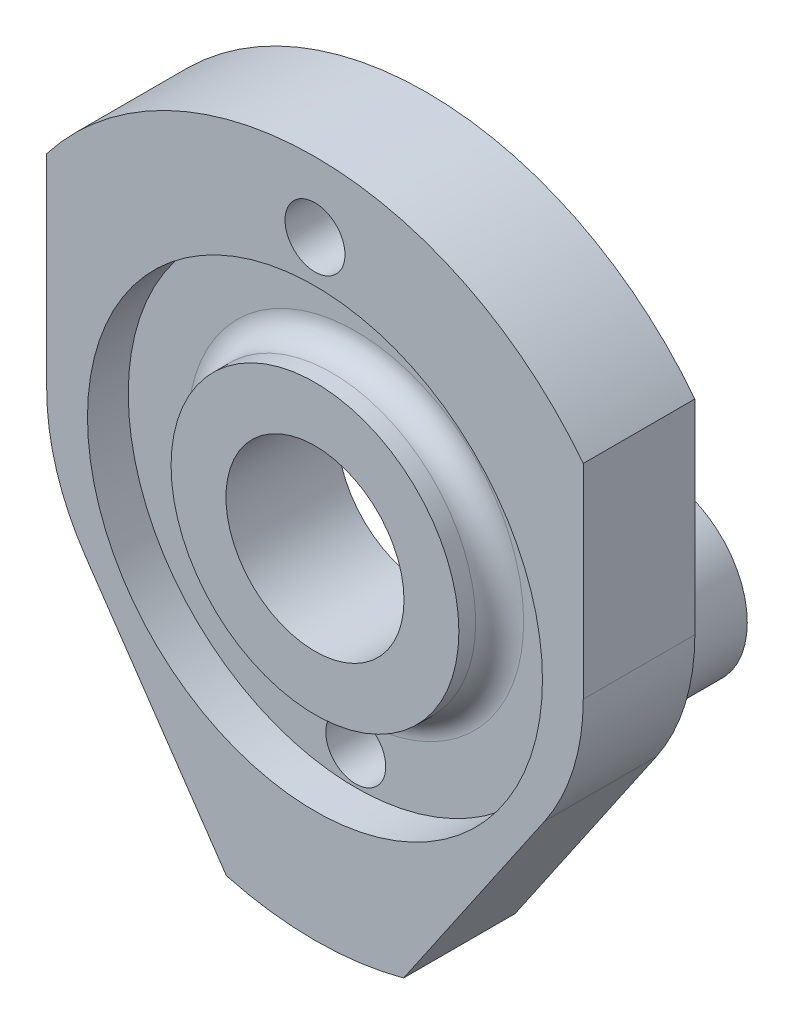
SolidWorks part; units mm, degrees
ref_plane "Front Plane" through (0, 0, 0) normal (0, 0, 1) x (1, 0, 0)
ref_plane "Top Plane" through (0, 0, 0) normal (0, 1, 0) x (1, 0, 0)
ref_plane "Right Plane" through (0, 0, 0) normal (1, 0, 0) x (0, 0, -1)
sketch "Sketch1" plane through (0, 0, 0) normal (0, 0, 1) x (1, 0, 0)
  line L1 (0, 0) -> (5.3097, 0) construction
  line L3 (44.7444, 34.6627) -> (44.7444, 0.6173)
  line L4 (-44.74, 0.611) -> (-44.74, 34.6683)
  line L5 (-14.7812, -54.6358) -> (-38.299, -20.2273)
  line L6 (14.7812, -54.6358) -> (38.3034, -20.2209)
  arc A0 (-14.7812, -54.6358) -> (14.7812, -54.6358) centre (0, 0) ccw
  circle A1 centre (0, 44.95) radius 5
  circle A2 centre (0, 0) radius 14.85
  arc A3 (-44.74, 0.611) -> (-38.299, -20.2273) centre (-7.8109, 0.611) ccw
  arc A4 (44.7444, 0.6173) -> (38.3034, -20.2209) centre (7.8153, 0.6173) cw
  arc A5 (44.7444, 34.6627) -> (-44.74, 34.6683) centre (0, 0) ccw
extrude "Boss-Extrude1" add sketch "Sketch1" against normal blind 18.61
sketch "Sketch3" plane through (0, 0, 0) normal (0, 0, 1) x (1, 0, 0)
  circle A0 centre (0, 0) radius 37.94
  circle A1 centre (0, 0) radius 24
extrude "Cut-Extrude1" cut sketch "Sketch3" against normal blind 6.8
sketch "Sketch4" plane through (0, 0, -6.8) normal (0, 0, 1) x (1, 0, 0)
  line L0 (0, 0) -> (0, -32.4) construction
  circle A0 centre (0, -32.4) radius 14.35
extrude "Boss-Extrude2" add sketch "Sketch4" against normal blind 50.95
sketch "Sketch5" plane through (0, 0, -6.8) normal (0, 0, 1) x (1, 0, 0)
  line L0 (0, 0) -> (0, -32.4) construction
  circle A0 centre (0, -32.4) radius 5
extrude "Cut-Extrude2" cut sketch "Sketch5" against normal blind 27.24
fillet "Fillet1" radius 4 1 edges at (24, 0, -6.8)
